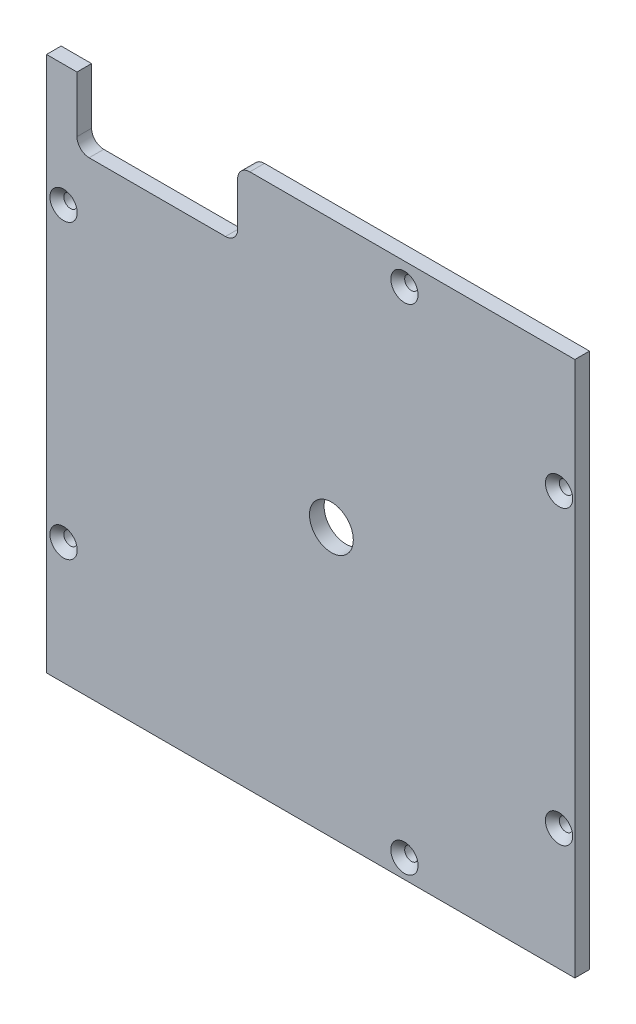
SolidWorks part; units mm, degrees
material "Water"
ref_plane "Plano frontal" through (0, 0, 0) normal (0, 0, 1) x (1, 0, 0)
ref_plane "Plano superior" through (0, 0, 0) normal (0, 1, 0) x (1, 0, 0)
ref_plane "Plano direito" through (0, 0, 0) normal (1, 0, 0) x (0, 0, -1)
sketch "Esboço1" plane through (0, 0, 0) normal (0, 0, 1) x (1, 0, 0)
  line L1 (-117, 110) -> (100, 110)
  line L2 (-117, 110) -> (-117, -110)
  line L3 (-117, -110) -> (100, -110)
  line L4 (100, 110) -> (100, -110)
extrude "Ressalto-extrusão1" add sketch "Esboço1" along normal blind 6
hole_wizard "Escareado para SFHCS M51" positions "Esboço4" profile "Esboço3" countersink size "M5" standard "Ansi Metric" end condition through all
sketch "Esboço4" plane through (0, 0, 6) normal (0, 0, 1) x (1, 0, 0)
  point P0 (-110, -60)
  point P2 (-110, 60)
  point P4 (93.5, 60)
  point P6 (93.5, -60)
  point P8 (30, -102.1949)
  point P10 (30, 100.8276)
  dimension "D2" = 30
  dimension "D3" = 60
  dimension "D4" = 60
  dimension "D5" = 110
  dimension "D6" = 93.5
sketch "Esboço3" plane through (-110, -60, 6) normal (1, 0, 0) x (0, -1, 0)
  line L0 (0, 0) -> (0, 6)
  line L1 (0, 6) -> (2.75, 6)
  line L2 (2.75, 6) -> (2.75, 2.85)
  line L3 (2.75, 2.85) -> (5.6, 0)
  line L5 (5.6, 0) -> (0, 0)
  line L6 (-2.75, 2.85) -> (-5.6, 0) construction
  line L11 (0, -6.35) -> (0, 107.95) construction
  dimension "Thru Hole Dia." = 5.5
  dimension "Thru Hole Depth" = 6
  dimension "Near C'Sink Dia." = 11.2
  dimension "Near C'Sink Angle" = 90
sketch "Esboço5" plane through (0, 0, 6) normal (0, 0, 1) x (1, 0, 0)
  line L0 (100, -110) -> (100, 110) construction
  line L1 (-117, -110) -> (100, -110) construction
  circle A0 centre (0, 0.3) radius 9
  dimension "D3" = 18
  dimension "D1" = 100
  dimension "D2" = 110.3
extrude "Corte-extrusão1" cut sketch "Esboço5" against normal up to next
sketch "Esboço6" plane through (0, 0, 6) normal (0, 0, 1) x (1, 0, 0)
  line L0 (100, 110) -> (-117, 110) construction
  line L1 (-104.5, 110) -> (-38.5, 110)
  line L2 (-104.5, 110) -> (-104.5, 82)
  line L3 (-104.5, 82) -> (-38.5, 82)
  line L4 (-38.5, 110) -> (-38.5, 82)
  dimension "D1" = 12.5
  dimension "D2" = 28
  dimension "D3" = 66
extrude "Corte-extrusão2" cut sketch "Esboço6" against normal through all
fillet "Filete1" radius 5 3 edges at (-38.5, 82, 3) (-38.5, 110, 3) (-104.5, 82, 3)
